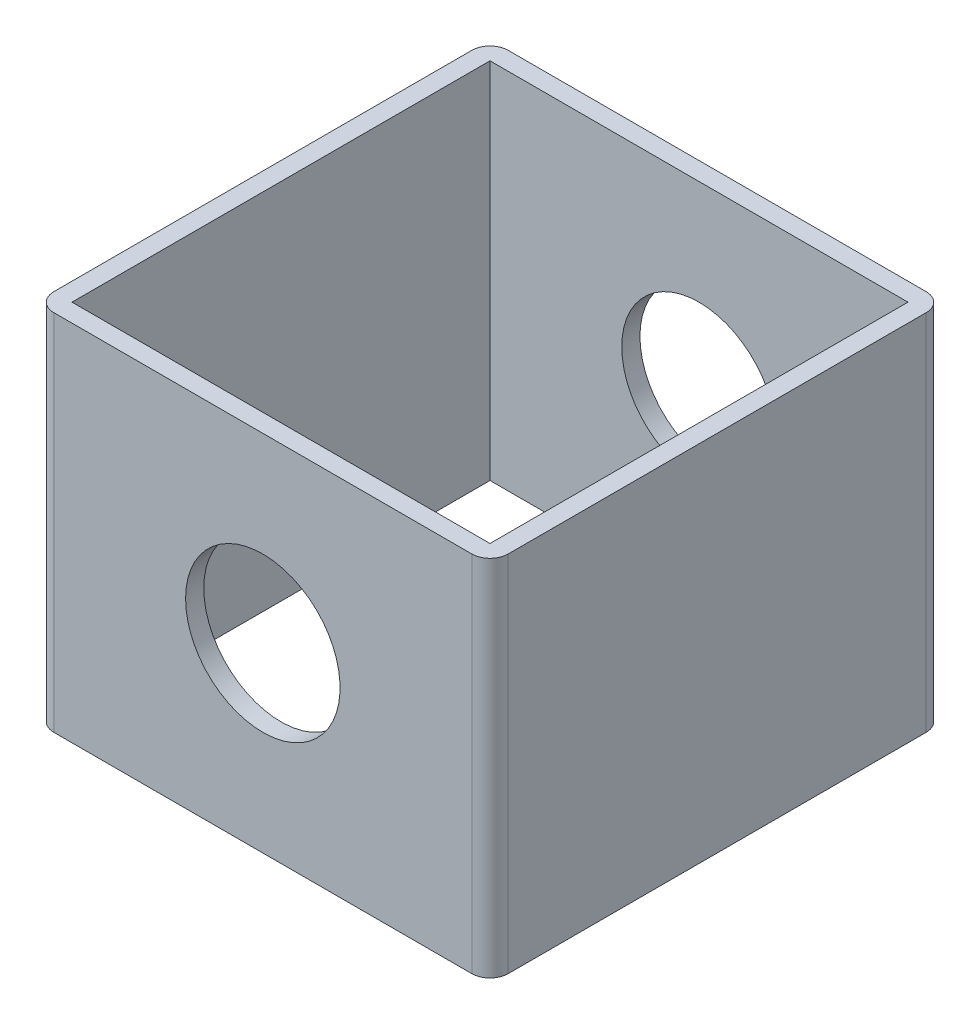
SolidWorks part; units mm, degrees
material "Plain Carbon Steel"
ref_plane "Front Plane" through (0, 0, 0) normal (0, 0, 1) x (1, 0, 0)
ref_plane "Top Plane" through (0, 0, 0) normal (0, 1, 0) x (1, 0, 0)
ref_plane "Right Plane" through (0, 0, 0) normal (1, 0, 0) x (0, 0, -1)
sketch "Sketch1" plane through (0, 0, 0) normal (0, 1, 0) x (1, 0, 0)
  line L1 (23, -25) -> (-23, -25)
  line L2 (25, -23) -> (25, 23)
  line L3 (23, 25) -> (-23, 25)
  line L4 (-25, -23) -> (-25, 23)
  line L5 (25, -25) -> (-25, 25) construction
  line L6 (25, 25) -> (-25, -25) construction
  arc A0 (-23, -25) -> (-25, -23) centre (-23, -23) cw
  arc A1 (23, -25) -> (25, -23) centre (23, -23) ccw
  arc A2 (25, 23) -> (23, 25) centre (23, 23) ccw
  arc A3 (-23, 25) -> (-25, 23) centre (-23, 23) ccw
  point P0 (0, 0)
  dimension "D2" = 2
  dimension "D1" = 50
extrude "Extrude-Thin1" add sketch "Sketch1" along normal mid plane 40 thin
sketch "Sketch2" plane through (0, 0, 23) normal (0, 0, -1) x (-1, 0, 0)
  circle A0 centre (0, 0) radius 8.5
  dimension "D1" = 17
extrude "Cut-Extrude1" cut sketch "Sketch2" against normal through all both and the other way through all
